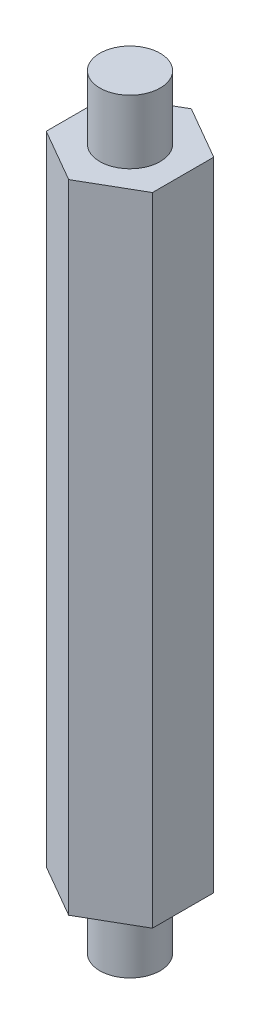
SolidWorks part; units mm, degrees
ref_plane "Front Plane" through (0, 0, 0) normal (0, 0, 1) x (1, 0, 0)
ref_plane "Top Plane" through (0, 0, 0) normal (0, 1, 0) x (1, 0, 0)
ref_plane "Right Plane" through (0, 0, 0) normal (1, 0, 0) x (0, 0, -1)
sketch "Sketch2" plane through (0, 0, 0) normal (0, 1, 0) x (1, 0, 0)
  line L1 (0, 2.8868) -> (-2.5, 1.4434)
  line L2 (-2.5, 1.4434) -> (-2.5, -1.4434)
  line L3 (-2.5, -1.4434) -> (0, -2.8868)
  line L4 (0, -2.8868) -> (2.5, -1.4434)
  line L5 (2.5, -1.4434) -> (2.5, 1.4434)
  line L6 (2.5, 1.4434) -> (0, 2.8868)
  circle A0 centre (0, 0) radius 2.5 construction
  dimension "D1" = 5
extrude "Boss-Extrude1" add sketch "Sketch2" along normal blind 30
sketch "Sketch3" plane through (0, 30, 0) normal (0, 1, 0) x (1, 0, 0)
  circle A0 centre (0, 0) radius 1.42
  dimension "D1" = 2.84
extrude "Boss-Extrude2" add sketch "Sketch3" along normal blind 3
sketch "Sketch4" plane through (0, 0, 0) normal (0, -1, 0) x (-1, 0, 0)
  circle A0 centre (0, 0) radius 1.42
  dimension "D1" = 2.84
extrude "Boss-Extrude3" add sketch "Sketch4" along normal blind 3
